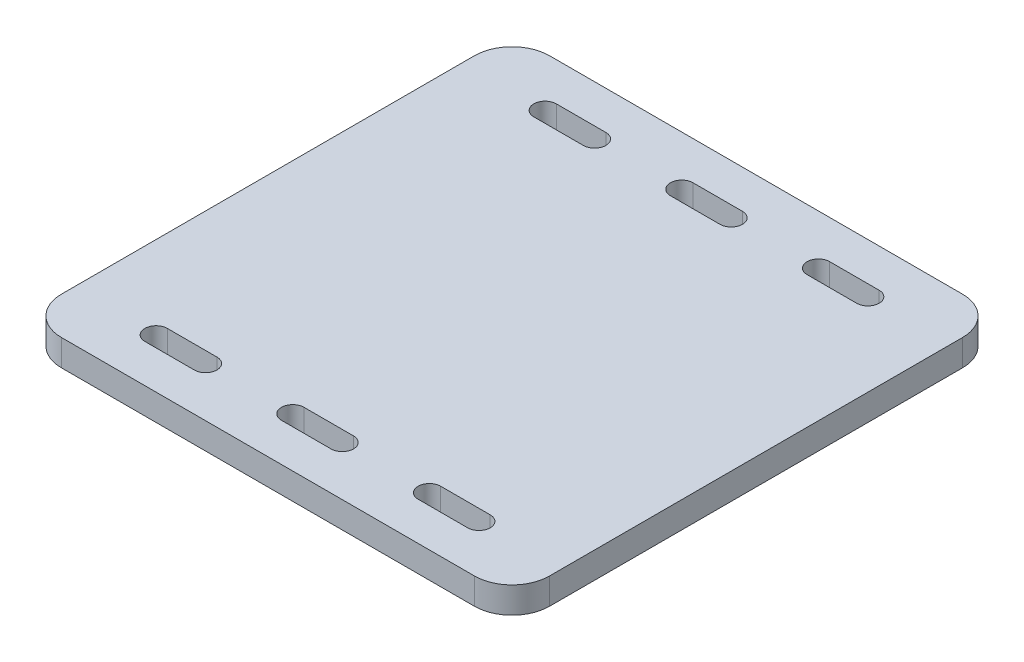
SolidWorks part; units mm, degrees
ref_plane "Front" through (0, 0, 0) normal (0, 0, 1) x (1, 0, 0)
ref_plane "Top" through (0, 0, 0) normal (0, 1, 0) x (1, 0, 0)
ref_plane "Right" through (0, 0, 0) normal (1, 0, 0) x (0, 0, -1)
sketch "Sketch1" plane through (0, 0, 0) normal (0, 1, 0) x (1, 0, 0)
  line L0 (-21.5, -24.4) -> (-14.9, -24.4)
  line L1 (-27.5, 32.5) -> (27.5, 32.5)
  line L2 (-32.5, 27.5) -> (-32.5, -27.5)
  line L3 (-27.5, -32.5) -> (27.5, -32.5)
  line L4 (32.5, 27.5) -> (32.5, -27.5)
  line L5 (-32.5, 32.5) -> (32.5, -32.5) construction
  line L6 (-32.5, -32.5) -> (32.5, 32.5) construction
  line L7 (-21.5, -27.4) -> (-14.9, -27.4)
  line L8 (-55, 0) -> (55, 0) construction
  line L9 (0, -55) -> (0, 55) construction
  line L10 (21.5, -27.4) -> (14.9, -27.4)
  line L11 (21.5, -24.4) -> (14.9, -24.4)
  line L12 (21.5, 24.4) -> (14.9, 24.4)
  line L13 (21.5, 27.4) -> (14.9, 27.4)
  line L14 (-21.5, 27.4) -> (-14.9, 27.4)
  line L15 (-21.5, 24.4) -> (-14.9, 24.4)
  line L16 (-3.3, -24.4) -> (3.3, -24.4)
  line L17 (-3.3, -27.4) -> (3.3, -27.4)
  line L18 (-3.3, 27.4) -> (3.3, 27.4)
  line L19 (-3.3, 24.4) -> (3.3, 24.4)
  arc A0 (-21.5, -24.4) -> (-21.5, -27.4) centre (-21.5, -25.9) ccw
  arc A1 (-14.9, -27.4) -> (-14.9, -24.4) centre (-14.9, -25.9) ccw
  arc A2 (21.5, -24.4) -> (21.5, -27.4) centre (21.5, -25.9) cw
  arc A3 (14.9, -27.4) -> (14.9, -24.4) centre (14.9, -25.9) cw
  arc A4 (-27.5, 32.5) -> (-32.5, 27.5) centre (-27.5, 27.5) ccw
  arc A5 (27.5, 32.5) -> (32.5, 27.5) centre (27.5, 27.5) cw
  arc A6 (27.5, -32.5) -> (32.5, -27.5) centre (27.5, -27.5) ccw
  arc A7 (-32.5, -27.5) -> (-27.5, -32.5) centre (-27.5, -27.5) ccw
  arc A8 (21.5, 24.4) -> (21.5, 27.4) centre (21.5, 25.9) ccw
  arc A9 (14.9, 27.4) -> (14.9, 24.4) centre (14.9, 25.9) ccw
  arc A10 (-21.5, 24.4) -> (-21.5, 27.4) centre (-21.5, 25.9) cw
  arc A11 (-14.9, 27.4) -> (-14.9, 24.4) centre (-14.9, 25.9) cw
  arc A12 (-3.3, -24.4) -> (-3.3, -27.4) centre (-3.3, -25.9) ccw
  arc A13 (3.3, -27.4) -> (3.3, -24.4) centre (3.3, -25.9) ccw
  arc A14 (-3.3, 24.4) -> (-3.3, 27.4) centre (-3.3, 25.9) cw
  arc A15 (3.3, 27.4) -> (3.3, 24.4) centre (3.3, 25.9) cw
  point P0 (0, 0)
  point P49 (0, 0)
  point P51 (0, 0)
  point P54 (0, -24.4)
  point P55 (0, 0)
  dimension "D3" = 3
  dimension "D4" = 6.6
  dimension "D6" = 5
  dimension "D7" = 3
  dimension "D1" = 65
  dimension "D2" = 11
  dimension "D5" = 6.6
  dimension "D8" = 6.6
extrude "Boss-Extrude1" add sketch "Sketch1" along normal blind 3.5
